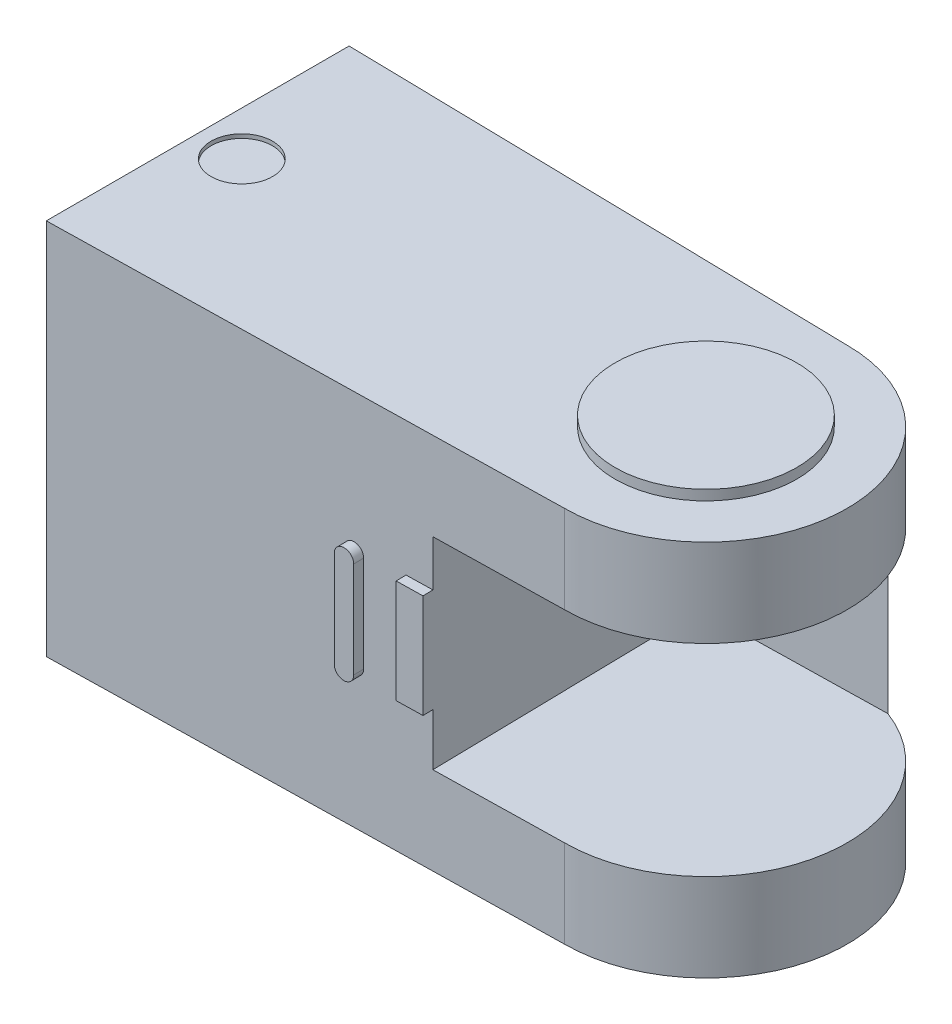
SolidWorks part; units mm, degrees
ref_plane "Front Plane" through (0, 0, 0) normal (0, 0, 1) x (1, 0, 0)
ref_plane "Top Plane" through (0, 0, 0) normal (0, 1, 0) x (1, 0, 0)
ref_plane "Right Plane" through (0, 0, 0) normal (1, 0, 0) x (0, 0, -1)
sketch "Sketch1" plane through (0, 0, 0) normal (0, 1, 0) x (1, 0, 0)
  line L0 (0, 70) -> (-251.7691, 75)
  line L1 (-251.7691, 75) -> (-251.7691, -75)
  line L2 (-251.7691, -75) -> (0, -70)
  line L3 (0, 0) -> (-292.5751, 0) construction
  arc A0 (0, -70) -> (0, 70) centre (0, 0) ccw
  dimension "D1" = 150
  dimension "D2" = 140
extrude "Boss-Extrude1" add sketch "Sketch1" against normal blind 187
sketch "Sketch2" plane through (1.3896, 0, 69.9724) normal (0.0199, 0, 0.9998) x (0.9998, 0, -0.0199)
  line L0 (-65.3899, -93.5) -> (-287.2879, -93.5) construction
  line L1 (-1.3899, -187) -> (-1.3899, 0) construction
  line L2 (-1.3899, -43.5) -> (169.277, -43.5)
  line L3 (-1.3899, -43.5) -> (-65.3899, -43.5)
  line L5 (-1.3899, -143.5) -> (-65.3899, -143.5)
  line L6 (-65.3899, -43.5) -> (-65.3899, -143.5)
  line L7 (169.277, -43.5) -> (169.277, -143.5)
  line L8 (169.277, -143.5) -> (-1.3899, -143.5)
  dimension "D1" = 100
  dimension "D2" = 64
extrude "Cut-Extrude3" cut sketch "Sketch2" against normal blind 135
sketch "Sketch3" plane through (-1.2909, 0, -65.001) normal (0.0199, 0, 0.9998) x (0.9998, 0, -0.0199)
  line L0 (-65.3899, -43.5) -> (143.5139, -43.5)
  line L1 (-65.3899, -43.5) -> (-65.3899, -143.5) construction
  line L2 (-65.3899, -43.5) -> (-65.3899, -143.5) construction
  line L3 (143.5139, -43.5) -> (143.5139, -143.5)
  line L4 (143.5139, -143.5) -> (-65.3899, -143.5)
  line L5 (-65.3899, -143.5) -> (-65.3899, -43.5)
extrude "Cut-Extrude4" cut sketch "Sketch3" along normal blind 175
sketch "Sketch4" plane through (0, 0, 0) normal (0, 1, 0) x (1, 0, 0)
  circle A0 centre (0, 0) radius 45
extrude "Boss-Extrude2" add sketch "Sketch4" along normal blind 5
sketch "Sketch5" plane through (0, -187, 0) normal (0, -1, 0) x (1, 0, 0)
  circle A0 centre (0, 0) radius 45
extrude "Boss-Extrude3" add sketch "Sketch5" along normal blind 5
sketch "Sketch6" plane through (1.3896, 0, 69.9724) normal (0.0199, 0, 0.9998) x (0.9998, 0, -0.0199)
  line L0 (-65.3899, -43.5) -> (-65.3899, -143.5) construction
  line L1 (-65.3899, -117.6891) -> (-78.4416, -117.6891)
  line L2 (-65.3899, -117.6891) -> (-65.3899, -66.3434)
  line L3 (-65.3899, -66.3434) -> (-78.4416, -66.3434)
  line L4 (-78.4416, -117.6891) -> (-78.4416, -66.3434)
extrude "Boss-Extrude4" add sketch "Sketch6" along normal blind 5
sketch "Sketch7" plane through (1.3896, 0, 69.9724) normal (0.0199, 0, 0.9998) x (0.9998, 0, -0.0199)
  line L0 (-103.7744, -116.7995) -> (-103.7744, -69.1725) construction
  line L1 (-108.5082, -116.7995) -> (-108.5082, -69.1725)
  line L2 (-99.0405, -116.7995) -> (-99.0405, -69.1725)
  arc A0 (-108.5082, -116.7995) -> (-99.0405, -116.7995) centre (-103.7744, -116.7995) ccw
  arc A1 (-99.0405, -69.1725) -> (-108.5082, -69.1725) centre (-103.7744, -69.1725) ccw
  point P2 (-103.7744, -92.986)
extrude "Boss-Extrude5" add sketch "Sketch7" along normal blind 5
sketch "Sketch8" plane through (0, 0, 0) normal (0, 1, 0) x (1, 0, 0)
  circle A0 centre (-229.9283, 0) radius 15.225
extrude "Cut-Extrude6" cut sketch "Sketch8" against normal blind 2
